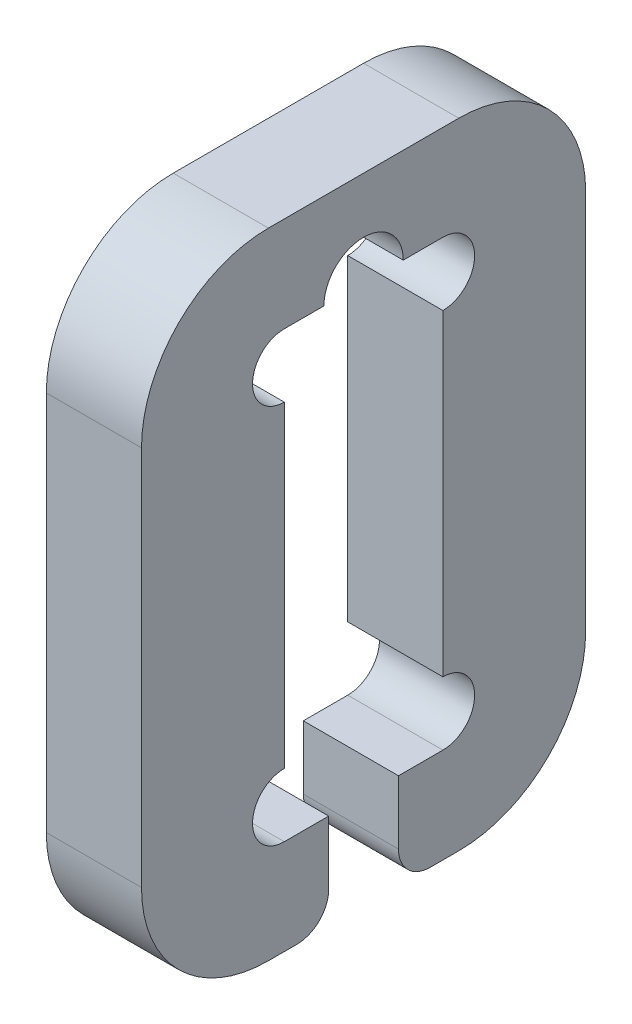
SolidWorks part; units mm, degrees
ref_plane "정면" through (0, 0, 0) normal (0, 0, 1) x (1, 0, 0)
ref_plane "윗면" through (0, 0, 0) normal (0, 1, 0) x (1, 0, 0)
ref_plane "우측면" through (0, 0, 0) normal (1, 0, 0) x (0, 0, -1)
sketch "스케치1" plane through (0, 0, 0) normal (1, 0, 0) x (0, 0, -1)
  line L1 (0, 0) -> (14, 0)
  line L2 (0, 0) -> (0, 20)
  line L3 (0, 20) -> (14, 20)
  line L4 (14, 0) -> (14, 20)
  dimension "D1" = 14
  dimension "D2" = 20
extrude "보스-돌출1" add sketch "스케치1" along normal blind 3
sketch "스케치2" plane through (3, 0, 0) normal (1, 0, 0) x (0, 0, -1)
  line L0 (7, 20) -> (7, 0) construction
  line L1 (14, 20) -> (0, 20) construction
  line L2 (0, 0) -> (14, 0) construction
  line L3 (4.5, 17) -> (4.5, 3)
  line L4 (4.5, 17) -> (9.5, 17)
  line L5 (4.5, 3) -> (9.5, 3)
  line L6 (9.5, 17) -> (9.5, 3)
  line L7 (4.5, 17) -> (9.5, 3) construction
  line L8 (4.5, 3) -> (9.5, 17) construction
  point P7 (7, 10)
  dimension "D1" = 5
  dimension "D2" = 3
  dimension "D3" = 14
extrude "컷-돌출1" cut sketch "스케치2" against normal blind 3
sketch "스케치3" plane through (3, 0, 0) normal (1, 0, 0) x (0, 0, -1)
  line L0 (9.5, 3) -> (9.5, 17) construction
  line L1 (4.5, 17) -> (4.5, 3) construction
  circle A0 centre (9.5, 16) radius 1
  circle A1 centre (4.5, 16) radius 1
  circle A2 centre (4.5, 4) radius 1
  circle A3 centre (9.5, 4) radius 1
  dimension "D1" = 2
extrude "컷-돌출2" cut sketch "스케치3" against normal blind 3
sketch "스케치4" plane through (3, 0, 0) normal (1, 0, 0) x (0, 0, -1)
  line L0 (7, 3) -> (7, 0) construction
  line L1 (4.5, 3) -> (9.5, 3) construction
  line L2 (0, 0) -> (14, 0) construction
  line L4 (5.9, 0) -> (8.1, 0)
  line L5 (5.9, 0) -> (5.9, 3)
  line L6 (5.9, 3) -> (8.1, 3)
  line L7 (8.1, 0) -> (8.1, 3)
  line L8 (5.9, 0) -> (8.1, 3) construction
  line L9 (5.9, 3) -> (8.1, 0) construction
  point P6 (7, 1.5)
  dimension "D1" = 2.2
extrude "컷-돌출3" cut sketch "스케치4" against normal blind 3
fillet "필렛1" radius 4 4 edges at (1.5, 0, 0) (1.5, 0, -14) (1.5, 20, -14) (1.5, 20, 0)
fillet "필렛2" radius 1 2 edges at (1.5, 0, -5.9) (1.5, 0, -8.1)
sketch "스케치5" plane through (3, 0, 0) normal (1, 0, 0) x (0, 0, -1)
  line L0 (9.5, 17) -> (4.5, 17) construction
  circle A0 centre (7, 17) radius 1.25
  dimension "D1" = 2.5
extrude "컷-돌출4" cut sketch "스케치5" against normal blind 10
